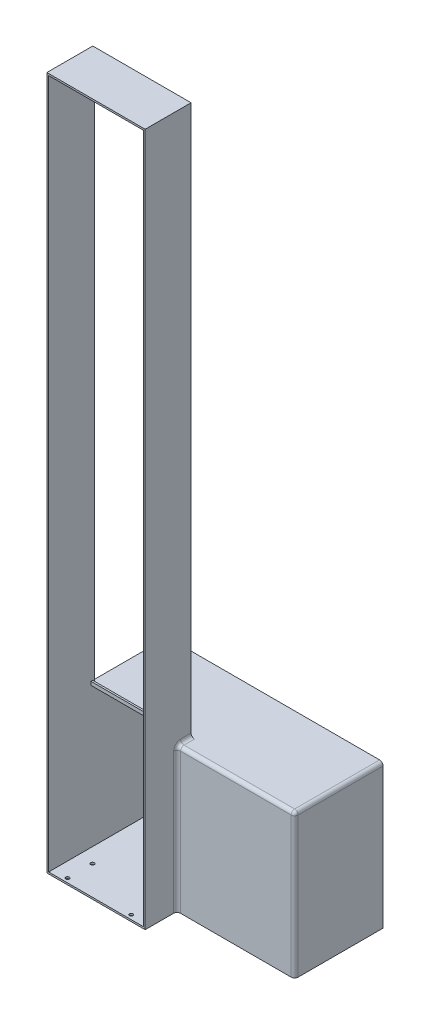
SolidWorks part; units mm, degrees
ref_plane "Front Plane" through (0, 0, 0) normal (0, 0, 1) x (1, 0, 0)
ref_plane "Top Plane" through (0, 0, 0) normal (0, 1, 0) x (1, 0, 0)
ref_plane "Right Plane" through (0, 0, 0) normal (1, 0, 0) x (0, 0, -1)
sketch "Pulley link" plane through (0, 0, 0) normal (0, 0, 1) x (1, 0, 0)
  line L0 (0, 850) -> (0, -850) construction
  line L1 (105, 850) -> (105, -850)
  line L2 (-105, 850) -> (-105, -850)
  arc A0 (105, 850) -> (-105, 850) centre (0, 850) ccw
  arc A1 (-105, -850) -> (105, -850) centre (0, -850) ccw
  point P3 (0, 0)
  point P8 (0, 0)
  dimension "D2" = 105
  dimension "D1" = 1700
sketch "Sketch3" plane through (0, -985.6187, 0) normal (0, -1, 0) x (1, 0, 0)
  line L0 (-140, 90.3875) -> (140, 90.3875)
  line L1 (140, 90.3875) -> (140, -0.5375)
  line L2 (140, -0.5375) -> (474.951, -0.5375)
  line L3 (474.951, -0.5375) -> (474.951, -252.6145)
  line L4 (474.951, -252.6145) -> (-140, -252.6145)
  line L5 (-140, -252.6145) -> (-140, 90.3875)
  line L6 (-120, 34.4098) -> (-120, 15.5898) construction
  line L7 (108, 90.3875) -> (-113, 90.3875) construction
  line L8 (120, 34.4098) -> (120, 15.5898) construction
  line L9 (393.3, -10.5375) -> (193.3, -10.5375) construction
  line L10 (464.951, -178.2255) -> (464.951, -20.9995) construction
  line L11 (400.943, -242.6145) -> (337.443, -242.6145) construction
  circle A0 centre (88, -194.6125) radius 5 construction
  circle A1 centre (-93, -194.6125) radius 5 construction
  circle A2 centre (88, 7.3875) radius 5 construction
  circle A3 centre (-93, 7.3875) radius 5 construction
  circle A4 centre (-93, 78.3875) radius 5 construction
  circle A5 centre (88, 78.3875) radius 5 construction
  circle A6 centre (88, -194.6125) radius 5
  circle A7 centre (-93, -194.6125) radius 5
  circle A8 centre (88, 7.3875) radius 5
  circle A9 centre (-93, 7.3875) radius 5
  circle A10 centre (-93, 78.3875) radius 5
  circle A11 centre (88, 78.3875) radius 5
  dimension "D1" = 20
  dimension "D2" = 20
  dimension "D3" = 10
  dimension "D4" = 10
  dimension "D5" = 10
extrude "Bottom plate" add sketch "Sketch3" along normal blind 5
sketch "Sketch4" plane through (0, -985.6187, 0) normal (0, 1, 0) x (1, 0, 0)
  line L6 (-135, 252.6145) -> (-135, -90.3875)
  line L7 (135, -90.3875) -> (135, 5.5375)
  line L8 (135, 5.5375) -> (469.951, 5.5375)
  line L9 (469.951, 5.5375) -> (469.951, 252.6145)
  line L10 (-135, 252.6145) -> (-140, 252.6145)
  line L11 (135, -90.3875) -> (140, -90.3875)
  line L18 (-140, 252.6145) -> (-140, -90.3875)
  line L19 (-140, -90.3875) -> (140, -90.3875)
  line L20 (140, -90.3875) -> (140, 0.5375)
  line L21 (140, 0.5375) -> (474.951, 0.5375)
  line L22 (474.951, 0.5375) -> (474.951, 252.6145)
  line L23 (474.951, 252.6145) -> (-140, 252.6145)
  line L24 (-140, 252.6145) -> (-140, -90.3875)
  line L25 (-140, -90.3875) -> (-135, -90.3875)
  line L26 (140, -90.3875) -> (140, 0.5375)
  line L27 (140, 0.5375) -> (474.951, 0.5375)
  line L28 (474.951, 0.5375) -> (474.951, 252.6145)
  line L29 (474.951, 252.6145) -> (469.951, 252.6145)
  dimension "D2" = 5
  dimension "D3" = 5
  dimension "D4" = 5
  dimension "D5" = 5
  dimension "D1" = 0
extrude "Vertical walls" add sketch "Sketch4" along normal blind 400
sketch "Sketch6" plane through (0, -585.6187, 0) normal (0, 1, 0) x (1, 0, 0)
  line L0 (135, -90.3875) -> (135, 35.3945)
  line L1 (-135, 252.6145) -> (469.951, 252.6145) construction
  line L2 (135, 252.6145) -> (474.951, 252.6145)
  line L3 (474.951, 252.6145) -> (474.951, 0.5375)
  line L4 (-140, 252.6145) -> (-140, -90.3875)
  line L5 (-140, -90.3875) -> (-135, -90.3875)
  line L6 (-135, -90.3875) -> (-135, 252.6145)
  line L7 (-135, 252.6145) -> (-140, 252.6145)
  line L8 (-140, 252.6145) -> (-140, -90.3875)
  line L9 (-140, -90.3875) -> (-135, -90.3875)
  line L10 (-135, -90.3875) -> (-135, 35.3945)
  line L11 (-135, 252.6145) -> (-140, 252.6145)
  line L12 (474.951, 0.5375) -> (140, 0.5375)
  line L13 (140, 0.5375) -> (140, -90.3875)
  line L14 (140, -90.3875) -> (135, -90.3875)
  line L15 (-135, 252.6145) -> (135, 252.6145)
  line L16 (135, 35.3945) -> (-135, 35.3945)
  point P19 (0, 0)
  dimension "D2" = 217.22
  dimension "D1" = 0
extrude "Mid horizontal plate" add sketch "Sketch6" along normal blind 5
sketch "Sketch7" plane through (0, -580.6187, 0) normal (0, 1, 0) x (1, 0, 0)
  line L18 (135, -90.3875) -> (135, 40.3945)
  line L19 (135, 40.3945) -> (140, 40.3945)
  line L20 (140, 40.3945) -> (140, -90.3875)
  line L21 (140, -90.3875) -> (135, -90.3875)
  line L22 (140, -90.3875) -> (140, 0.5375) construction
  line L24 (-135, 35.3945) -> (135, 35.3945) construction
  line L26 (-140, -90.3875) -> (-135, -90.3875)
  line L28 (-135, -90.3875) -> (-135, 40.3945)
  line L30 (-135, -90.3875) -> (-135, 252.6145) construction
  line L32 (-135, 40.3945) -> (-140, 40.3945)
  line L34 (-140, 252.6145) -> (-140, -90.3875) construction
  line L35 (-140, 40.3945) -> (-140, -90.3875)
  dimension "D1" = 5
  dimension "D2" = 5
extrude "Rest of vertical extrude" add sketch "Sketch7" along normal blind 1560
sketch "Sketch8" plane through (0, 979.3813, 0) normal (0, 1, 0) x (1, 0, 0)
  line L5 (-140, -90.3875) -> (140, -90.3875)
  line L6 (-140, -90.3875) -> (-140, 40.3945)
  line L7 (-140, 40.3945) -> (140, 40.3945)
  line L8 (140, -90.3875) -> (140, 40.3945)
extrude "Top plate" add sketch "Sketch8" along normal blind 5
fillet "Motor box fillets" radius 10 5 edges at (474.951, -785.6187, -0.5375) (474.951, -580.6187, -126.576) (307.4755, -580.6187, -0.5375) (140, -580.6187, -20.466) (140, -785.6187, -0.5375)
sketch "Sketch10" plane through (135, 0, 0) normal (-1, 0, 0) x (0, 0, 1)
  line L0 (-35.3945, -585.6187) -> (-5.5375, -585.6187) construction
  line L1 (-35.3945, -585.6187) -> (-30.3945, -585.6187)
  line L2 (-35.3945, -585.6187) -> (-35.3945, -575.6187)
  line L3 (-35.3945, -575.6187) -> (-30.3945, -575.6187)
  line L4 (-30.3945, -585.6187) -> (-30.3945, -575.6187)
  dimension "D1" = 10
  dimension "D2" = 5
extrude "Bottom plate lip" add sketch "Sketch10" along normal up to surface (270 mm away) up to face at (-135, -293.1187, -59.504)
